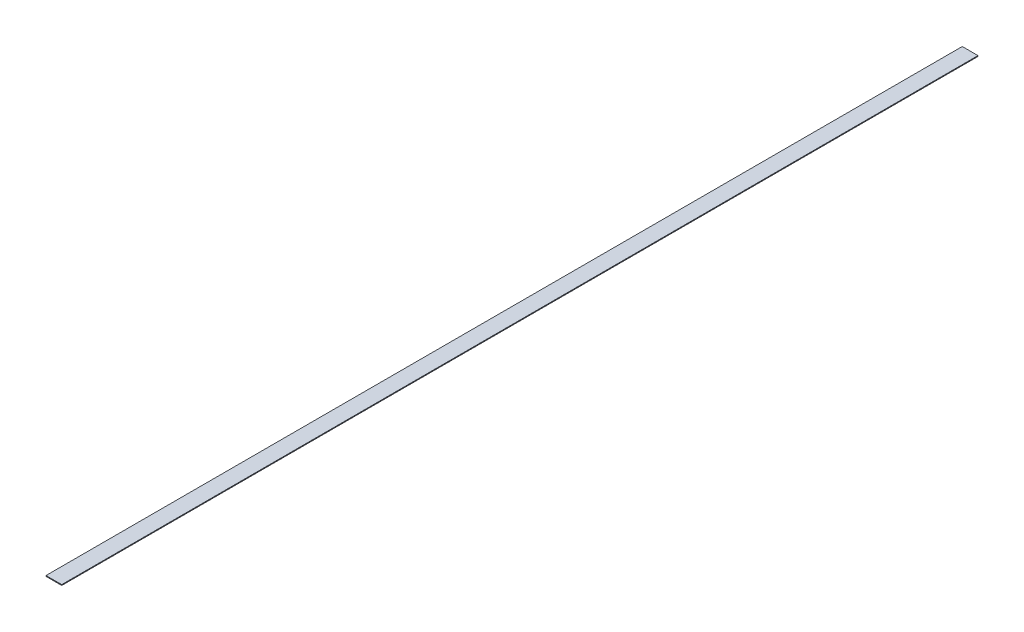
SolidWorks part; units mm, degrees
ref_plane "Front Plane" through (0, 0, 0) normal (0, 0, 1) x (1, 0, 0)
ref_plane "Top Plane" through (0, 0, 0) normal (0, 1, 0) x (1, 0, 0)
ref_plane "Right Plane" through (0, 0, 0) normal (1, 0, 0) x (0, 0, -1)
sketch "Sketch1" plane through (0, 0, 0) normal (0, 1, 0) x (1, 0, 0)
  line L1 (-25.4, -1479.55) -> (25.4, -1479.55)
  line L2 (-25.4, -1479.55) -> (-25.4, 1479.55)
  line L3 (-25.4, 1479.55) -> (25.4, 1479.55)
  line L4 (25.4, -1479.55) -> (25.4, 1479.55)
  line L5 (-25.4, -1479.55) -> (25.4, 1479.55) construction
  line L6 (-25.4, 1479.55) -> (25.4, -1479.55) construction
  point P0 (0, 0)
  dimension "D1" = 2959.1
  dimension "D2" = 50.8
extrude "Boss-Extrude1" add sketch "Sketch1" along normal blind 2.54
